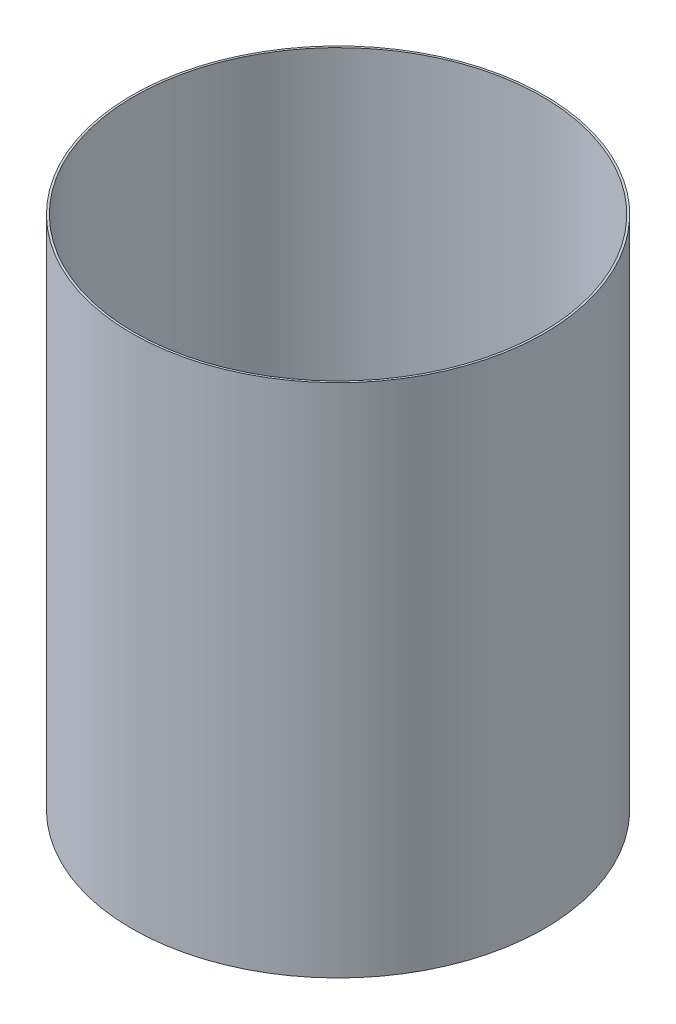
SolidWorks part; units mm, degrees
ref_plane "Front Plane" through (0, 0, 0) normal (0, 0, 1) x (1, 0, 0)
ref_plane "Top Plane" through (0, 0, 0) normal (0, 1, 0) x (1, 0, 0)
ref_plane "Right Plane" through (0, 0, 0) normal (1, 0, 0) x (0, 0, -1)
sketch "Sketch1" plane through (0, 0, 0) normal (0, 1, 0) x (1, 0, 0)
  circle A0 centre (0, 0) radius 10
  circle A1 centre (0, 0) radius 9.9
  dimension "D1" = 19.8
  dimension "D2" = 20
extrude "Boss-Extrude1" add sketch "Sketch1" along normal blind 25
